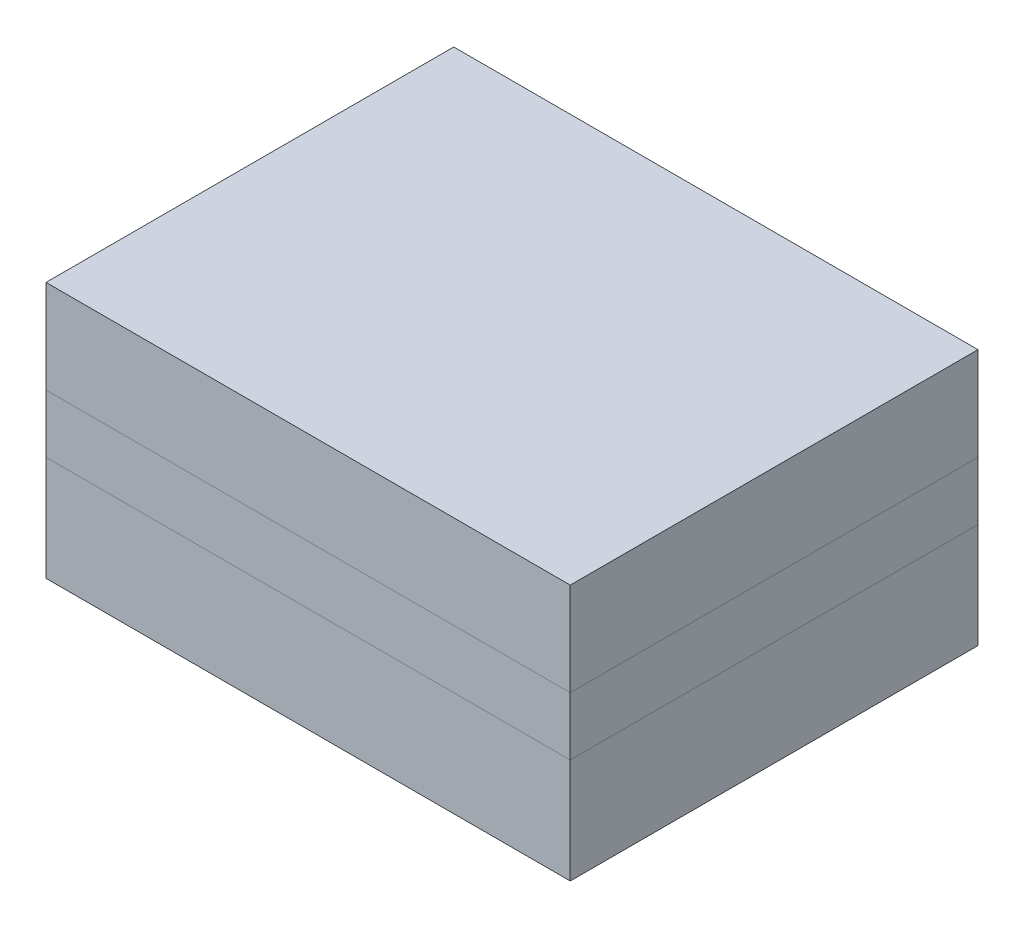
SolidWorks part; units mm, degrees
ref_plane "Front Plane" through (0, 0, 0) normal (0, 0, 1) x (1, 0, 0)
ref_plane "Top Plane" through (0, 0, 0) normal (0, 1, 0) x (1, 0, 0)
ref_plane "Right Plane" through (0, 0, 0) normal (1, 0, 0) x (0, 0, -1)
sketch "Sketch2" plane through (0, 0, 0) normal (0, 1, 0) x (1, 0, 0)
  line L1 (0, 0) -> (45, 0)
  line L2 (0, 0) -> (0, 35)
  line L3 (0, 35) -> (45, 35)
  line L4 (45, 0) -> (45, 35)
  dimension "D1" = 45
  dimension "D2" = 35
extrude "Boss-Extrude1" add sketch "Sketch2" along normal blind 9
sketch "Sketch5" plane through (0, 9, 0) normal (0, 1, 0) x (1, 0, 0)
  line L0 (10, 25) -> (10, 10)
  line L1 (0, 35) -> (45, 35)
  line L2 (0, 35) -> (0, 0)
  line L3 (0, 0) -> (45, 0)
  line L4 (45, 35) -> (45, 0)
  line L5 (10, 10) -> (35, 10)
  line L6 (35, 25) -> (35, 10)
  line L7 (10, 25) -> (35, 25)
  dimension "D1" = 10
extrude "Boss-Extrude4" add sketch "Sketch5" along normal blind 5 separate body
sketch "Sketch6" plane through (0, 14, 0) normal (0, 1, 0) x (1, 0, 0)
  line L1 (0, 35) -> (45, 35)
  line L2 (0, 35) -> (0, 0)
  line L3 (0, 0) -> (45, 0)
  line L4 (45, 35) -> (45, 0)
extrude "Boss-Extrude5" add sketch "Sketch6" along normal blind 8 separate body
